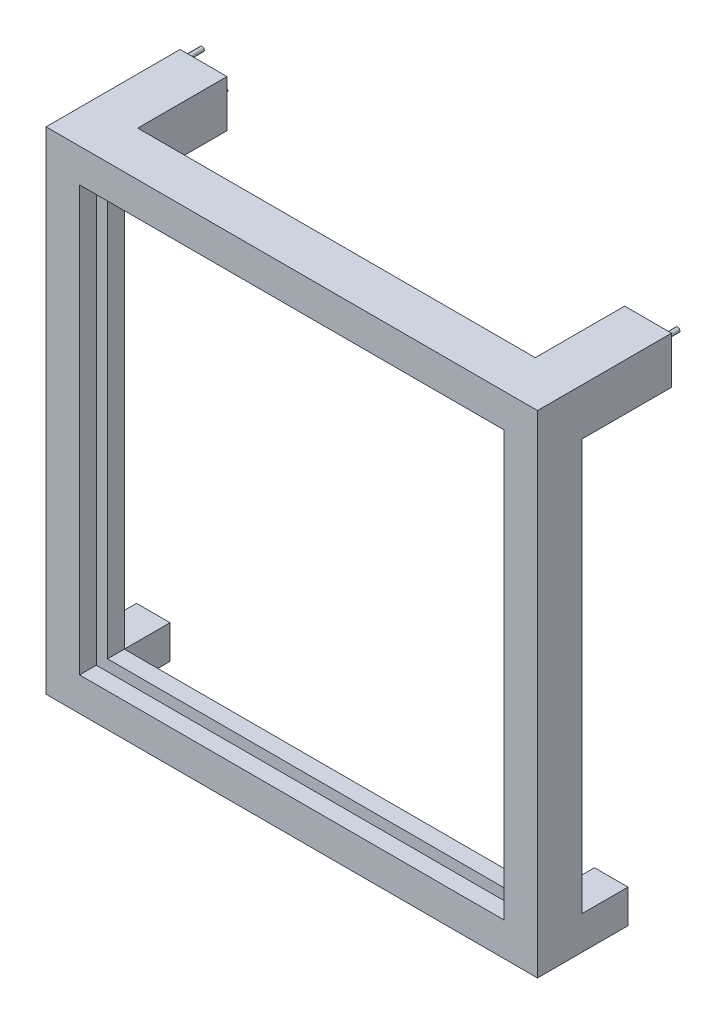
SolidWorks part; units mm, degrees
ref_plane "Plan de face" through (0, 0, 0) normal (0, 0, 1) x (1, 0, 0)
ref_plane "Plan de dessus" through (0, 0, 0) normal (0, 1, 0) x (1, 0, 0)
ref_plane "Plan de droite" through (0, 0, 0) normal (1, 0, 0) x (0, 0, -1)
sketch "Esquisse1" plane through (0, 0, 0) normal (0, 0, 1) x (1, 0, 0)
  line L1 (-190, -190) -> (190, -190)
  line L2 (-190, -190) -> (-190, 190)
  line L3 (-190, 190) -> (190, 190)
  line L4 (190, -190) -> (190, 190)
  line L5 (-190, -190) -> (190, 190) construction
  line L6 (-190, 190) -> (190, -190) construction
  line L7 (-220, -220) -> (220, -220)
  line L8 (-220, -220) -> (-220, 220)
  line L9 (-220, 220) -> (220, 220)
  line L10 (220, -220) -> (220, 220)
  line L11 (-220, -220) -> (220, 220) construction
  line L12 (-220, 220) -> (220, -220) construction
  point P0 (0, 0)
  point P6 (0, 0)
  dimension "D1" = 440
  dimension "D2" = 440
  dimension "D3" = 380
  dimension "D4" = 380
extrude "Boss.-Extru.1" add sketch "Esquisse1" along normal blind 40
sketch "Esquisse2" plane through (0, -190, 0) normal (0, 1, 0) x (1, 0, 0)
  line L0 (-190, -40) -> (190, -40) construction
  line L1 (-200, -25) -> (200, -25)
  line L2 (-200, -25) -> (-200, -15)
  line L3 (-200, -15) -> (200, -15)
  line L4 (200, -25) -> (200, -15)
  line L5 (220, 0) -> (-220, 0) construction
  line L6 (-220, -40) -> (-220, 0) construction
  line L7 (220, -40) -> (220, 0) construction
  dimension "D1" = 15
  dimension "D2" = 15
  dimension "D3" = 20
  dimension "D4" = 20
extrude "Enlèv. mat.-Extru.1" cut sketch "Esquisse2" along normal blind 390 and the other way blind 10
sketch "Esquisse3" plane through (0, 0, 0) normal (0, 0, -1) x (-1, 0, 0)
  line L0 (-220, -220) -> (-220, 220) construction
  line L9 (-220, 220) -> (-178, 220)
  line L10 (-220, 220) -> (-220, 178)
  line L11 (-220, 178) -> (-178, 178)
  line L12 (-178, 220) -> (-178, 178)
  line L13 (-220, 220) -> (220, 220) construction
  line L15 (220, 220) -> (178, 220)
  line L16 (220, 220) -> (220, 178)
  line L17 (220, 178) -> (178, 178)
  line L18 (178, 220) -> (178, 178)
  dimension "D1" = 42
  dimension "D2" = 42
  dimension "D3" = 42
  dimension "D4" = 42
extrude "Boss.-Extru.2" add sketch "Esquisse3" along normal blind 80
sketch "Esquisse5" plane through (0, 0, -80) normal (0, 0, -1) x (-1, 0, 0)
  line L0 (220, 220) -> (210.577, 210.577) construction
  line L1 (-220, 220) -> (-201.01, 201.01) construction
  line L2 (-201.01, 201.01) -> (-178, 178) construction
  line L3 (210.577, 210.577) -> (178, 178) construction
  circle A0 centre (-210.505, 210.505) radius 2
  circle A1 centre (-189.505, 189.505) radius 2
  circle A2 centre (215.2885, 215.2885) radius 2
  circle A3 centre (194.2885, 194.2885) radius 2
  point P18 (-201.01, 201)
  point P19 (210.577, 210.505)
  dimension "D1" = 4
  dimension "D2" = 4
  dimension "D3" = 4
  dimension "D4" = 4
extrude "Boss.-Extru.3" add sketch "Esquisse5" along normal blind 15
sketch "Esquisse7" plane through (0, 178, 0) normal (0, -1, 0) x (1, 0, 0)
  line L0 (178, -80) -> (178, -41) construction
  line L1 (-178, -80) -> (-178, -41) construction
  line L2 (-178, -80) -> (-178, 0) construction
  line L3 (-178, -41) -> (-220, -80) construction
  line L5 (178, -80) -> (178, 0) construction
  line L6 (178, -41) -> (220, -80) construction
  circle A0 centre (199, -60.5) radius 4
  circle A1 centre (-199, -60.5) radius 4
  dimension "D1" = 8
  dimension "D2" = 8
  dimension "D3" = 39
  dimension "D4" = 39
extrude "Enlèv. mat.-Extru.2" cut sketch "Esquisse7" against normal blind 20
sketch "Esquisse8" plane through (0, 0, 0) normal (0, 0, -1) x (-1, 0, 0)
  line L1 (-220, -220) -> (-190, -220)
  line L2 (-220, -220) -> (-220, -190)
  line L3 (-220, -190) -> (-190, -190)
  line L4 (-190, -220) -> (-190, -190)
  line L5 (190, -190) -> (220, -190)
  line L6 (190, -190) -> (190, -220)
  line L7 (190, -220) -> (220, -220)
  line L8 (220, -190) -> (220, -220)
extrude "Boss.-Extru.4" add sketch "Esquisse8" along normal blind 41
